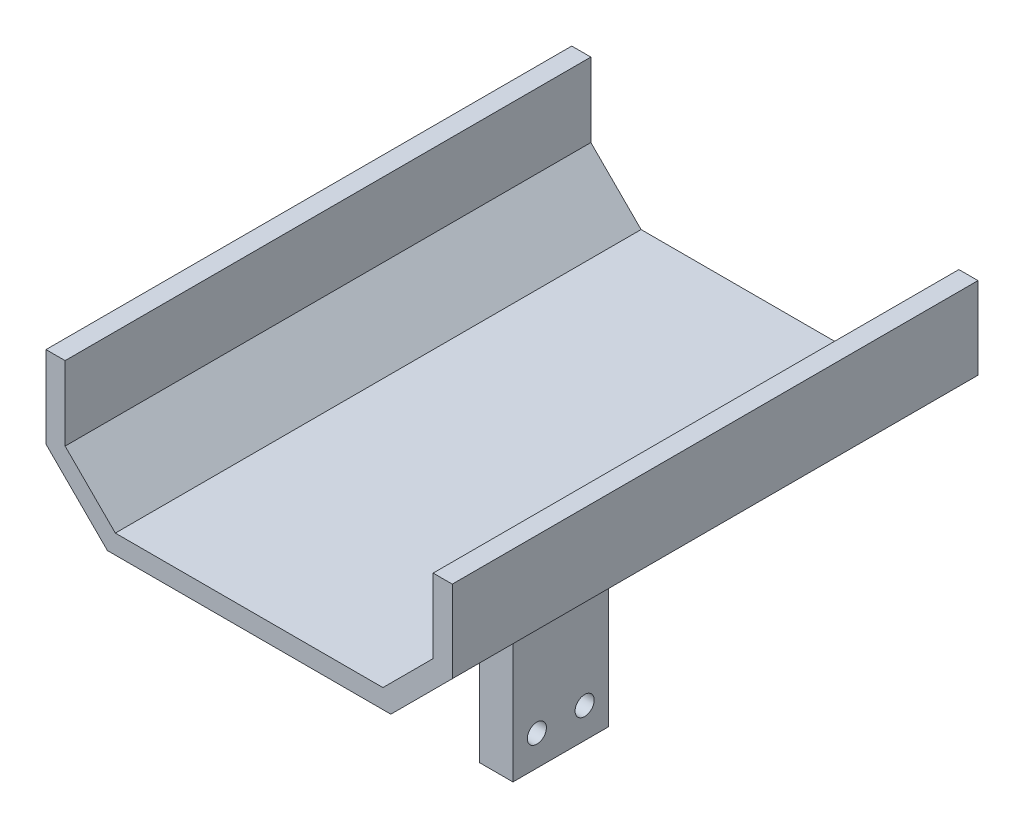
SolidWorks part; units mm, degrees
ref_plane "Front Plane" through (0, 0, 0) normal (0, 0, 1) x (1, 0, 0)
ref_plane "Top Plane" through (0, 0, 0) normal (0, 1, 0) x (1, 0, 0)
ref_plane "Right Plane" through (0, 0, 0) normal (1, 0, 0) x (0, 0, -1)
sketch "Sketch1" plane through (0, 0, 0) normal (0, 0, 1) x (1, 0, 0)
  line L0 (0, 0) -> (0, -17.1483)
  line L1 (0, -17.1483) -> (12.8517, -30)
  line L2 (12.8517, -30) -> (72.1483, -30)
  line L3 (72.1483, -30) -> (85, -17.1483)
  line L4 (85, -17.1483) -> (85, 0)
  line L5 (85, 0) -> (81, 0)
  line L6 (81, 0) -> (81, -15.4914)
  line L7 (81, -15.4914) -> (70.4914, -26)
  line L8 (70.4914, -26) -> (14.5086, -26)
  line L9 (14.5086, -26) -> (4, -15.4914)
  line L10 (4, -15.4914) -> (4, 0)
  line L11 (4, 0) -> (0, 0)
  point P13 (9.2543, -20.7457)
  point P14 (75.7457, -20.7457)
  point P15 (0, 0)
  dimension "D1" = 4
  dimension "D2" = 4
  dimension "D3" = 4
  dimension "D4" = 4
  dimension "D5" = 4
  dimension "D6" = 135
  dimension "D7" = 135
  dimension "D8" = 85
  dimension "D9" = 30
extrude "Boss-Extrude1" add sketch "Sketch1" along normal blind 110
sketch "Sketch2" plane through (0, -30, 0) normal (0, -1, 0) x (1, 0, 0)
  line L0 (12.8517, 110) -> (72.1483, 110) construction
  line L1 (3.3, 35) -> (10.3, 35)
  line L2 (3.3, 35) -> (3.3, 15)
  line L3 (3.3, 15) -> (10.3, 15)
  line L4 (10.3, 35) -> (10.3, 15)
  line L5 (75.7, 95) -> (82.7, 95)
  line L6 (75.7, 95) -> (75.7, 75)
  line L7 (75.7, 75) -> (82.7, 75)
  line L8 (82.7, 95) -> (82.7, 75)
  line L9 (0, 110) -> (0, 0) construction
  point P8 (82.7, 69.3485)
  point P13 (79.2, 95)
  dimension "D1" = 20
  dimension "D2" = 20
  dimension "D3" = 7
  dimension "D4" = 7
  dimension "D5" = 80
  dimension "D6" = 75
  dimension "D7" = 65.4
  dimension "D8" = 3.3
extrude "Boss-Extrude2" add sketch "Sketch2" against normal up to body separate body
sketch "Sketch4" plane through (0, -30, 0) normal (0, -1, 0) x (1, 0, 0)
  line L1 (3.3, 35) -> (10.3, 35)
  line L2 (3.3, 35) -> (3.3, 15)
  line L3 (3.3, 15) -> (10.3, 15)
  line L4 (10.3, 35) -> (10.3, 15)
  line L5 (75.7, 95) -> (82.7, 95)
  line L6 (75.7, 95) -> (75.7, 75)
  line L7 (75.7, 75) -> (82.7, 75)
  line L8 (82.7, 95) -> (82.7, 75)
extrude "Boss-Extrude3" add sketch "Sketch4" along normal blind 14.5
sketch "Sketch5" plane through (3.3, 0, 0) normal (-1, 0, 0) x (0, 0, 1)
  line L0 (35, -20.4483) -> (35, -44.5) construction
  line L2 (35, -44.5) -> (15, -44.5) construction
  circle A0 centre (20, -38.15) radius 2
  circle A1 centre (30, -38.15) radius 2
  circle A4 centre (80, -38.15) radius 2
  circle A5 centre (90, -38.15) radius 2
  dimension "D1" = 4
  dimension "D2" = 4
  dimension "D3" = 10
  dimension "D4" = 5
  dimension "D5" = 6.35
  dimension "D6" = 2
extrude "Cut-Extrude1" cut sketch "Sketch5" against normal through all both and the other way through all
